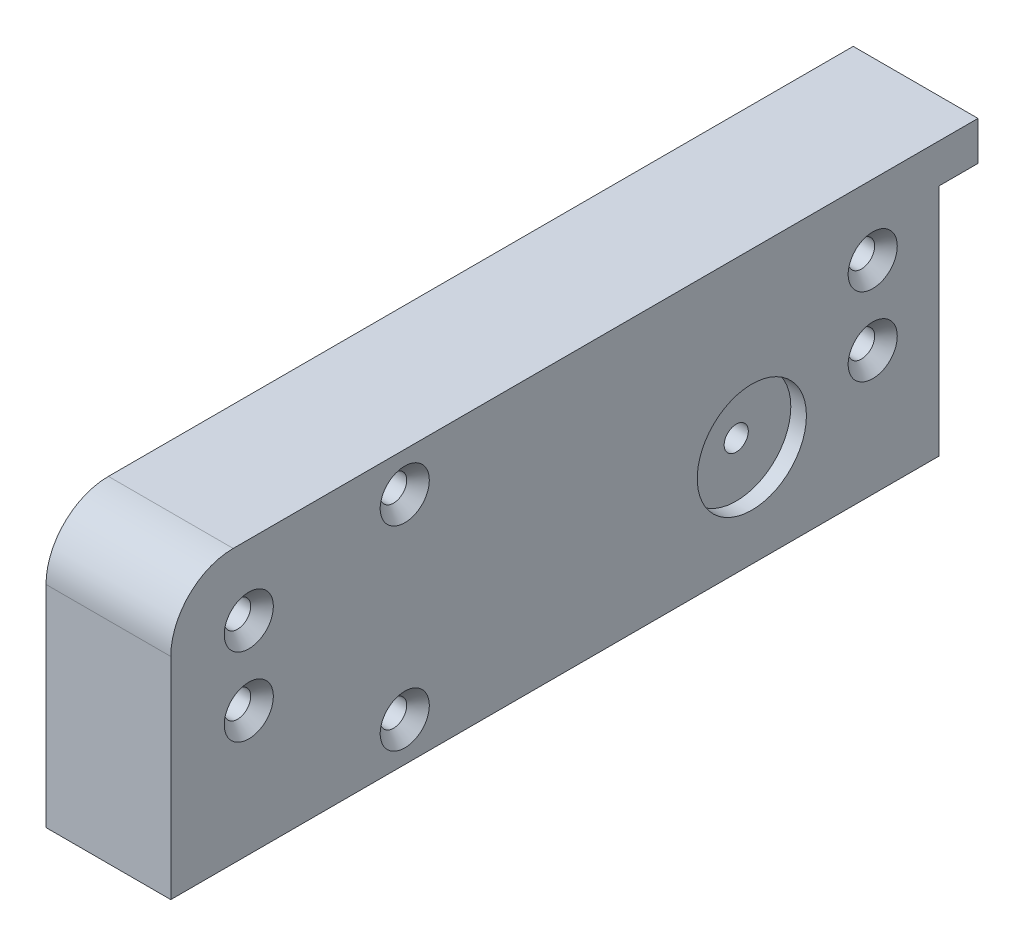
SolidWorks part; units mm, degrees
ref_plane "Front Plane" through (0, 0, 0) normal (0, 0, 1) x (1, 0, 0)
ref_plane "Top Plane" through (0, 0, 0) normal (0, 1, 0) x (1, 0, 0)
ref_plane "Right Plane" through (0, 0, 0) normal (1, 0, 0) x (0, 0, -1)
sketch "Sketch1" plane through (0, 0, 0) normal (1, 0, 0) x (0, 0, -1)
  line L0 (0, 0) -> (-98.5, 0)
  line L1 (-98.5, 0) -> (-98.5, 35)
  line L2 (-98.5, 35) -> (5, 35)
  line L3 (5, 35) -> (5, 30)
  line L4 (5, 30) -> (0, 30)
  line L5 (0, 30) -> (0, 0)
  dimension "D1" = 98.5
  dimension "D2" = 103.5
  dimension "D3" = 35
  dimension "D4" = 30
extrude "Boss-Extrude1" add sketch "Sketch1" along normal blind 16
sketch "Sketch2" plane through (16, 0, 0) normal (1, 0, 0) x (0, 0, -1)
  line L0 (-88.5, 26) -> (-88.5, 16) construction
  line L1 (-88.5, 16) -> (-8.5, 16) construction
  line L2 (-8.5, 16) -> (-8.5, 26) construction
  line L3 (-68.5, 30) -> (-68.5, 5) construction
  line L4 (0, 0) -> (0, 30) construction
  line L5 (5, 35) -> (-98.5, 35) construction
  dimension "D1" = 8.5
  dimension "D2" = 9
  dimension "D3" = 9
  dimension "D4" = 80
  dimension "D5" = 10
  dimension "D6" = 20
  dimension "D7" = 14
  dimension "D8" = 25
hole_wizard "CSK for M3 Countersunk Flat Head Screw1" positions "3DSketch1" profile "Sketch3" countersink size "M3" standard "DIN" end condition through all
sketch3d "3DSketch1"
  point P0 (16, 26, 88.5)
  point P3 (16, 16, 88.5)
  point P6 (16, 30, 68.5)
  point P9 (16, 5, 68.5)
  point P12 (16, 26, 8.5)
  point P15 (16, 16, 8.5)
sketch "Sketch3" plane through (16, 26, 88.5) normal (0, 1, 0) x (0, 0, -1)
  line L0 (0, 0) -> (0, 16)
  line L1 (0, 16) -> (1.7, 16)
  line L2 (1.7, 16) -> (1.7, 1.45)
  line L3 (1.7, 1.45) -> (3.15, 0)
  line L5 (3.15, 0) -> (0, 0)
  line L6 (-1.7, 1.45) -> (-3.15, 0) construction
  line L11 (0, -6.35) -> (0, 107.95) construction
  dimension "Thru Hole Dia." = 3.4
  dimension "Thru Hole Depth" = 16
  dimension "Near C'Sink Dia." = 6.3
  dimension "Near C'Sink Angle" = 90
sketch "Sketch4" plane through (0, 0, 0) normal (-1, 0, 0) x (0, 0, 1)
  line L0 (8.5, 26) -> (13.5, 26) construction
  line L1 (88.5, 26) -> (83.5, 26) construction
  line L2 (10.0875, 28.7496) -> (8.5, 26) construction
  line L3 (10.0875, 28.7496) -> (6.9125, 28.7496)
  line L4 (6.9125, 28.7496) -> (5.325, 26)
  line L5 (5.325, 26) -> (6.9125, 23.2504)
  line L6 (6.9125, 23.2504) -> (10.0875, 23.2504)
  line L7 (10.0875, 23.2504) -> (11.675, 26)
  line L8 (11.675, 26) -> (10.0875, 28.7496)
  line L9 (86.9125, 28.7496) -> (85.325, 26)
  line L10 (85.325, 26) -> (86.9125, 23.2504)
  line L11 (86.9125, 23.2504) -> (90.0875, 23.2504)
  line L12 (90.0875, 23.2504) -> (91.675, 26)
  line L13 (91.675, 26) -> (90.0875, 28.7496)
  line L14 (90.0875, 28.7496) -> (86.9125, 28.7496)
  line L15 (86.9125, 28.7496) -> (88.5, 26) construction
  circle A0 centre (8.5, 26) radius 3.175 construction
  circle A1 centre (88.5, 26) radius 3.175 construction
  dimension "D1" = 6.35
  dimension "D3" = 6.35
  dimension "D2" = 60
  dimension "D4" = 60
  dimension "D5" = 5
  dimension "D6" = 5
extrude "Cut-Extrude1" cut sketch "Sketch4" against normal blind 9
sketch "Sketch5" plane through (0, 0, 0) normal (-1, 0, 0) x (0, 0, 1)
  circle A0 centre (8.5, 26) radius 4.1
  circle A1 centre (88.5, 26) radius 4.1
  dimension "D1" = 8.2
  dimension "D2" = 8.2
extrude "Cut-Extrude2" cut sketch "Sketch5" against normal blind 6
sketch "Sketch6" plane through (16, 0, 0) normal (1, 0, 0) x (0, 0, -1)
  line L0 (-8.5, 26) -> (-8.5, 13) construction
  line L1 (-8.5, 13) -> (-24, 13) construction
  circle A0 centre (-24, 13) radius 1.55
  dimension "D3" = 3.1
  dimension "D1" = 13
  dimension "D2" = 15.5
extrude "Cut-Extrude3" cut sketch "Sketch6" against normal through all
sketch "Sketch7" plane through (16, 0, 0) normal (1, 0, 0) x (0, 0, -1)
  circle A0 centre (-24, 13) radius 7
  dimension "D1" = 14
extrude "Cut-Extrude4" cut sketch "Sketch7" against normal blind 2
fillet "Fillet1" radius 8 1 edges at (8, 35, 98.5)
